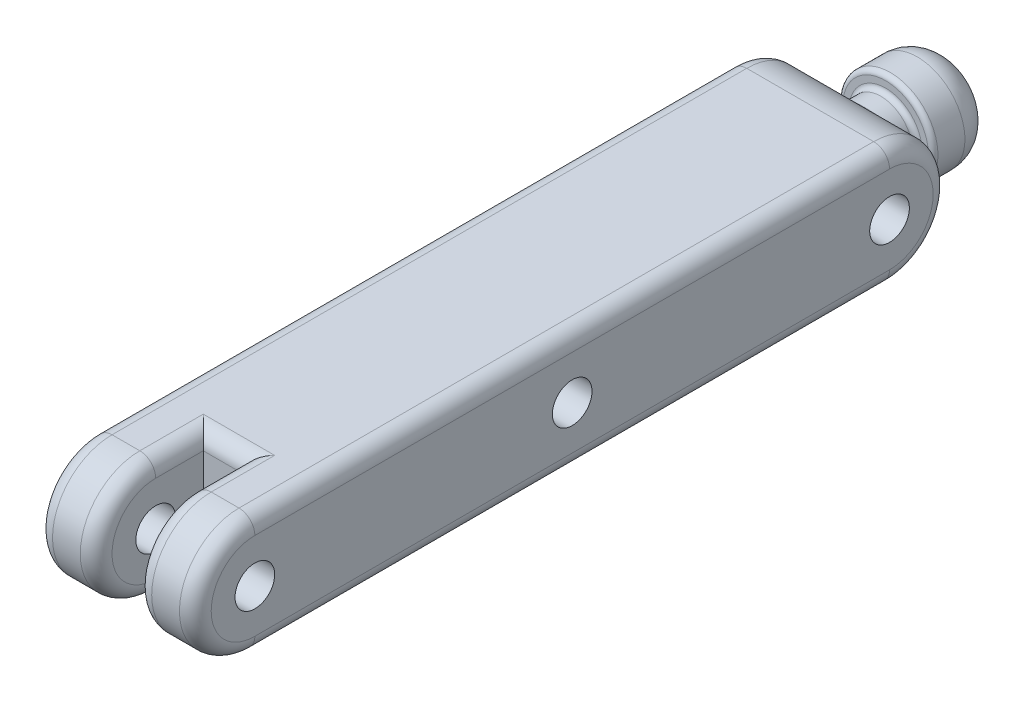
SolidWorks part; units mm, degrees
material "ABS"
ref_plane "Front" through (0, 0, 0) normal (0, 0, 1) x (1, 0, 0)
ref_plane "Top" through (0, 0, 0) normal (0, 1, 0) x (1, 0, 0)
ref_plane "Right" through (0, 0, 0) normal (1, 0, 0) x (0, 0, -1)
sketch "Sketch1" plane through (0, 0, 0) normal (1, 0, 0) x (0, 0, -1)
  line L0 (-25.4, 4.7625) -> (25.4, 4.7625)
  line L1 (25.4, -4.7625) -> (-25.4, -4.7625)
  circle A0 centre (0, 0) radius 1.5875
  circle A1 centre (25.4, 0) radius 1.5875
  arc A2 (25.4, 4.7625) -> (25.4, -4.7625) centre (25.4, 0) cw
  arc A3 (-25.4, 4.7625) -> (-25.4, -4.7625) centre (-25.4, 0) ccw
  circle A4 centre (-25.4, 0) radius 1.5875
  dimension "D1" = 3.175
  dimension "D2" = 25.4
  dimension "D3" = 9.525
  dimension "D4" = 25.4
extrude "Boss-Extrude1" add sketch "Sketch1" along normal blind 12.7
sketch3d "3DSketch1"
  line L0 (6.35, 4.7625, 25.4) -> (6.35, 4.7625, 21.59)
  line L1 (12.7, 4.7625, 25.4) -> (0, 4.7625, 25.4) construction
  line L2 (12.7, -4.7625, 25.4) -> (0, -4.7625, 25.4) construction
  line L3 (6.35, -4.7625, 21.59) -> (6.35, -4.7625, 25.4)
  line L4 (6.35, 4.7625, 21.59) -> (6.35, -4.7625, 21.59)
  arc A0 (6.35, 4.7625, 25.4) -> (6.35, -4.7625, 25.4) centre (6.35, 0, 25.4) ccw
  point P5 (11.1125, 0, 25.4)
  dimension "D1" = 3.81
extrude "Cut-Extrude1" cut sketch "3DSketch1" along direction (1, 0, 0) on the side against the normal mid plane 3.175
fillet "Fillet1" radius 1.27 15 edges at (12.7, 0, -30.1625) (12.7, -4.7625, 0) (12.7, 0, 30.1625) (0, 0, -30.1625) (0, -4.7625, 0) (0, 0, 30.1625) (12.7, 4.7625, 0) (0, 4.7625, 0)
ref_plane "Plane1" through (0, 0, -30.1625) normal (0, 0, -1) x (-1, 0, 0)
sketch "Sketch2" plane through (0, 0, -30.1625) normal (0, 0, -1) x (-1, 0, 0)
  line L0 (-11.43, 4.7625) -> (-11.43, -4.7625) construction
  line L1 (-11.43, 4.7625) -> (-1.27, 4.7625) construction
  circle A0 centre (-6.35, 0) radius 2.54
  point P4 (-11.43, 0)
  point P7 (-6.35, 4.7625)
  dimension "D1" = 5.08
extrude "Boss-Extrude2" add sketch "Sketch2" against normal up to body and the other way blind 1.27
sketch "Sketch6" plane through (0, 0, -31.4325) normal (0, 0, -1) x (-1, 0, 0)
  circle A0 centre (-6.35, 0) radius 3.81
  dimension "D1" = 7.62
extrude "Boss-Extrude3" add sketch "Sketch6" along normal blind 5.08
fillet "Fillet2" radius 2.54 1 edges at (2.54, 0, -36.5125)
fillet "Fillet3" radius 0.381 3 edges at (2.54, 0, -31.4325) (3.81, 0, -31.4325) (3.8191, 0.2148, -30.1577)
